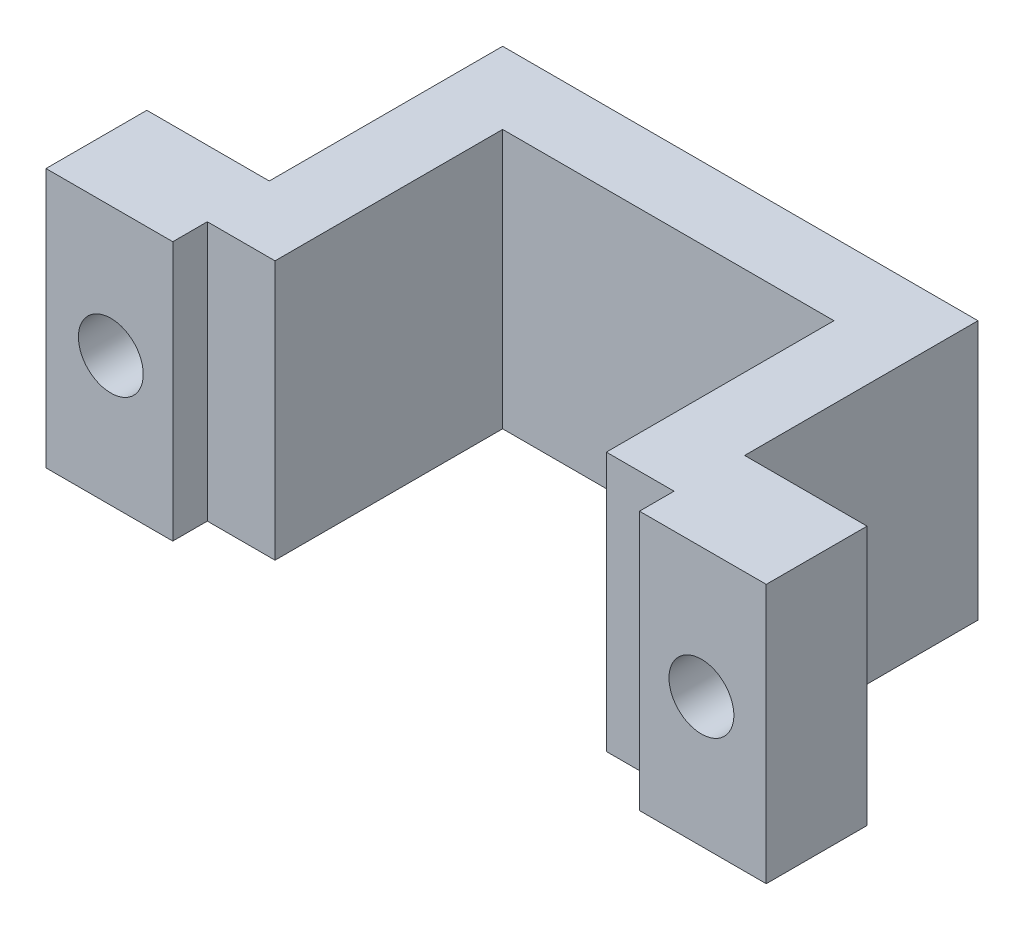
SolidWorks part; units mm, degrees
ref_plane "Front Plane" through (0, 0, 0) normal (0, 0, 1) x (1, 0, 0)
ref_plane "Top Plane" through (0, 0, 0) normal (0, 1, 0) x (1, 0, 0)
ref_plane "Right Plane" through (0, 0, 0) normal (1, 0, 0) x (0, 0, -1)
sketch "Sketch1" plane through (0, 0, 0) normal (0, 1, 0) x (1, 0, 0)
  line L0 (0, 0) -> (8.8, 0)
  line L1 (8.8, 0) -> (8.8, 2.4)
  line L2 (8.8, 2.4) -> (13.5, 2.4)
  line L3 (13.5, 2.4) -> (13.5, 18.2)
  line L4 (13.5, 18.2) -> (36.5, 18.2)
  line L5 (0, 0) -> (0, 7)
  line L6 (25, 31.9636) -> (25, 4.4364) construction
  line L7 (0, 7) -> (8.5, 7)
  line L8 (8.5, 7) -> (8.5, 23.2)
  line L9 (8.5, 23.2) -> (41.5, 23.2)
  line L10 (41.5, 7) -> (41.5, 23.2)
  line L11 (50, 7) -> (41.5, 7)
  line L12 (50, 0) -> (50, 7)
  line L13 (36.5, 2.4) -> (36.5, 18.2)
  line L14 (41.2, 2.4) -> (36.5, 2.4)
  line L15 (41.2, 0) -> (41.2, 2.4)
  line L16 (50, 0) -> (41.2, 0)
  point P11 (25, 18.2)
  point P15 (25, 23.2)
  point P19 (25, 18.2)
  dimension "D1" = 8.8
  dimension "D2" = 2.4
  dimension "D3" = 4.7
  dimension "D4" = 15.8
  dimension "D5" = 11.5
  dimension "D6" = 7
  dimension "D7" = 5
  dimension "D8" = 5
extrude "Boss-Extrude1" add sketch "Sketch1" along normal blind 18
sketch "Sketch2" plane through (0, 0, -7) normal (0, 0, -1) x (-1, 0, 0)
  line L0 (-50, 0) -> (-50, 18) construction
  line L1 (-50, 18) -> (-25, 0) construction
  line L2 (-41.5, 0) -> (-8.5, 0) construction
  line L3 (-25, 0) -> (-25, 18) construction
  line L4 (-41.5, 18) -> (-8.5, 18) construction
  line L5 (-25, 18) -> (0, 18) construction
  line L6 (0, 18) -> (0, 0) construction
  line L7 (-50, 9) -> (-45.5, 9) construction
  circle A0 centre (-45.5, 9) radius 2.25
  circle A1 centre (-4.5, 9) radius 2.25
  dimension "D1" = 4.5
  dimension "D2" = 4.5
extrude "Cut-Extrude1" cut sketch "Sketch2" against normal through all
